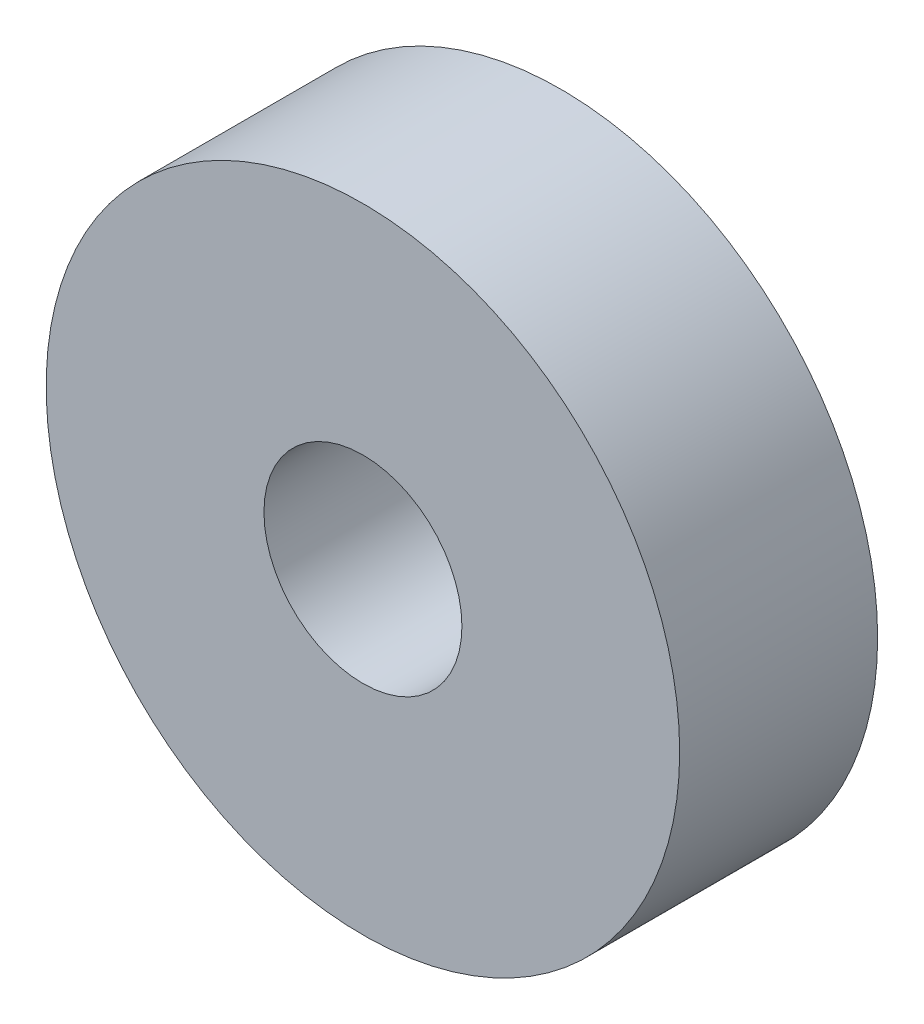
SolidWorks part; units mm, degrees
ref_plane "Front Plane" through (0, 0, 0) normal (0, 0, 1) x (1, 0, 0)
ref_plane "Top Plane" through (0, 0, 0) normal (0, 1, 0) x (1, 0, 0)
ref_plane "Right Plane" through (0, 0, 0) normal (1, 0, 0) x (0, 0, -1)
sketch "Sketch1" plane through (0, 0, 0) normal (0, 0, 1) x (1, 0, 0)
  circle A0 centre (0, 0) radius 8
  dimension "D1" = 16
extrude "Boss-Extrude1" add sketch "Sketch1" along normal mid plane 5
sketch "Sketch2" plane through (0, 0, 2.5) normal (0, 0, 1) x (1, 0, 0)
  circle A0 centre (0, 0) radius 2.5
  dimension "D1" = 5
extrude "Cut-Extrude1" cut sketch "Sketch2" against normal through all
